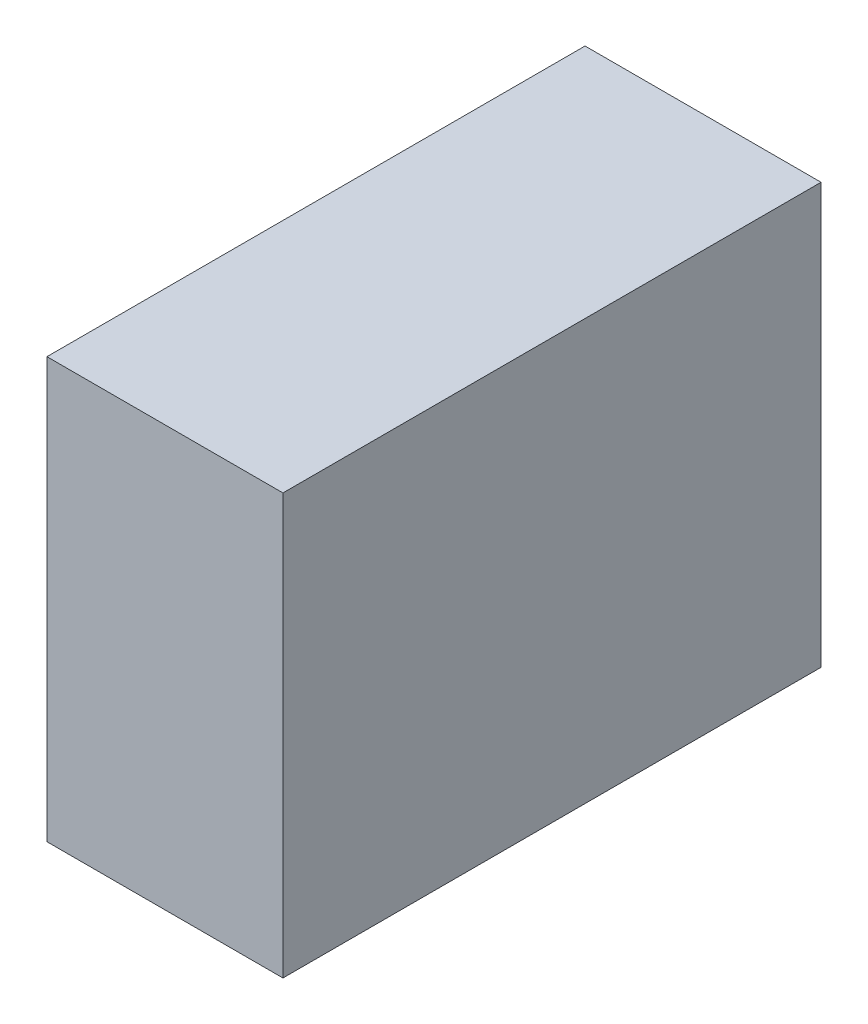
SolidWorks part; units mm, degrees
material "Porcelana cerâmica"
ref_plane "Plano frontal" through (0, 0, 0) normal (0, 0, 1) x (1, 0, 0)
ref_plane "Plano superior" through (0, 0, 0) normal (0, 1, 0) x (1, 0, 0)
ref_plane "Plano direito" through (0, 0, 0) normal (1, 0, 0) x (0, 0, -1)
sketch "Esboço1" plane through (0, 0, 0) normal (0, 0, 1) x (1, 0, 0)
  line L1 (0, 0) -> (50, 0)
  line L2 (0, 0) -> (0, 89)
  line L3 (0, 89) -> (50, 89)
  line L4 (50, 0) -> (50, 89)
  dimension "D1" = 89
  dimension "D2" = 50
extrude "Ressalto-extrusão1" add sketch "Esboço1" along normal blind 114
